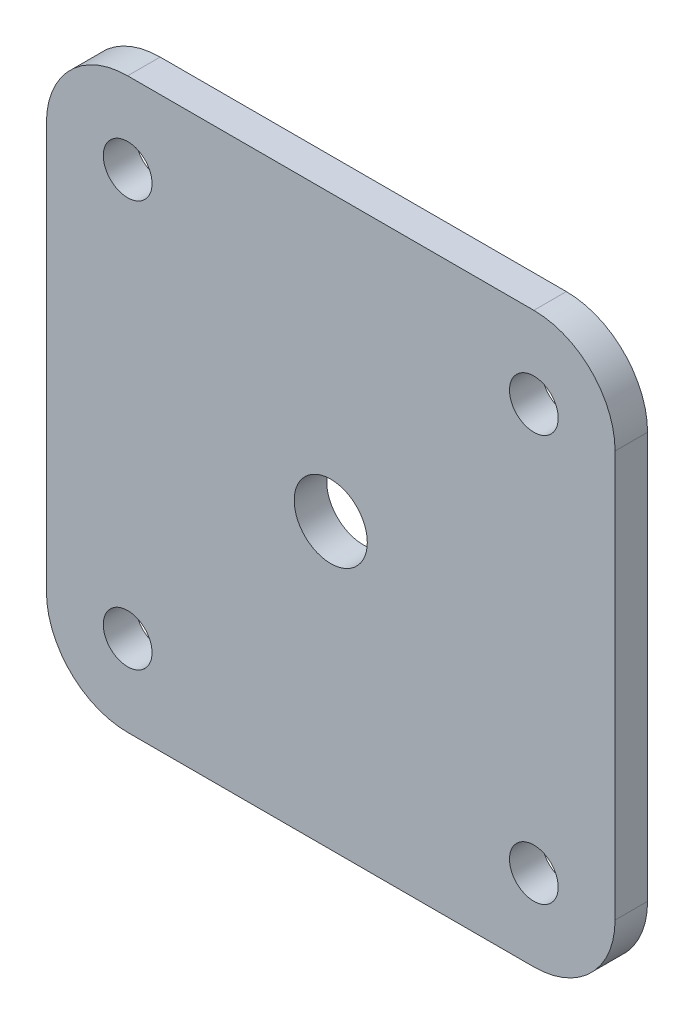
SolidWorks part; units mm, degrees
ref_plane "Alzado" through (0, 0, 0) normal (0, 0, 1) x (1, 0, 0)
ref_plane "Planta" through (0, 0, 0) normal (0, 1, 0) x (1, 0, 0)
ref_plane "Vista lateral" through (0, 0, 0) normal (1, 0, 0) x (0, 0, -1)
sketch "Croquis1" plane through (0, 0, 0) normal (0, 0, 1) x (1, 0, 0)
  line L1 (-17.5, -17.5) -> (17.5, -17.5)
  line L2 (-17.5, -17.5) -> (-17.5, 17.5)
  line L3 (-17.5, 17.5) -> (17.5, 17.5)
  line L4 (17.5, -17.5) -> (17.5, 17.5)
  line L5 (-17.5, -17.5) -> (17.5, 17.5) construction
  line L6 (-17.5, 17.5) -> (17.5, -17.5) construction
  circle A0 centre (0, 0) radius 2.25
  point P0 (0, 0)
  dimension "D2" = 4.5
  dimension "D1" = 35
extrude "Saliente-Extruir1" add sketch "Croquis1" along normal blind 2
fillet "Redondeo1" radius 5 4 edges at (-17.5, -17.5, 1) (17.5, -17.5, 1) (17.5, 17.5, 1) (-17.5, 17.5, 1)
sketch "Croquis2" plane through (0, 0, 2) normal (0, 0, 1) x (1, 0, 0)
  circle A0 centre (-12.5, 12.5) radius 1.5
  circle A1 centre (12.5, 12.5) radius 1.5
  circle A2 centre (12.5, -12.5) radius 1.5
  circle A3 centre (-12.5, -12.5) radius 1.5
  point P12 (0, 0)
  dimension "D1" = 3
  dimension "D2" = 4
extrude "Cortar-Extruir1" cut sketch "Croquis2" against normal through all
